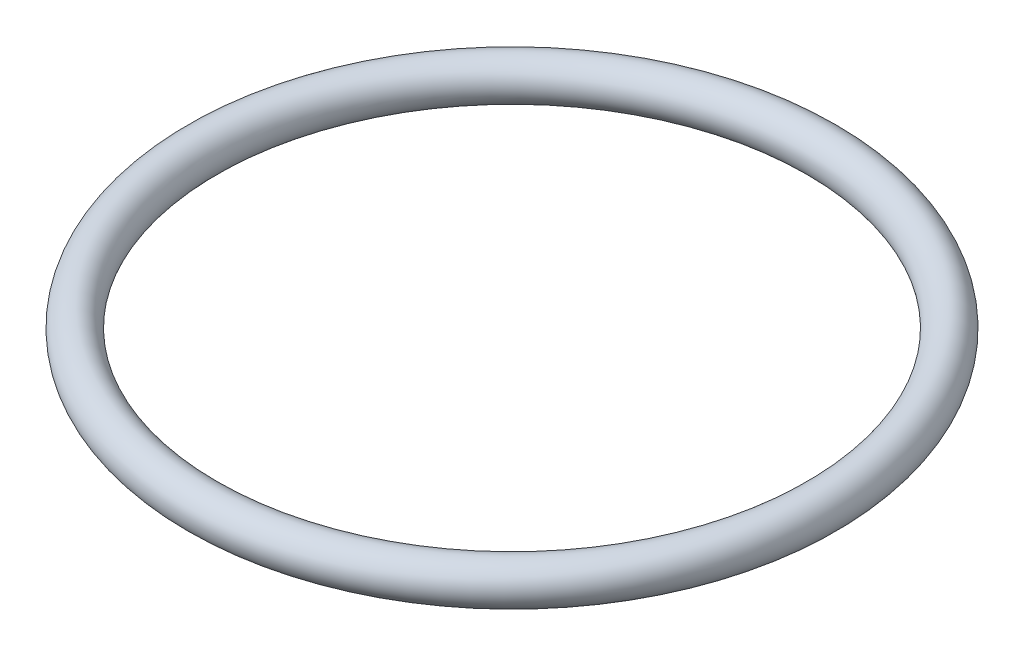
SolidWorks part; units mm, degrees
material "1060 Alloy"
ref_plane "Front Plane" through (0, 0, 0) normal (0, 0, 1) x (1, 0, 0)
ref_plane "Top Plane" through (0, 0, 0) normal (0, 1, 0) x (1, 0, 0)
ref_plane "Right Plane" through (0, 0, 0) normal (1, 0, 0) x (0, 0, -1)
sketch "Sketch1" plane through (0, 0, 0) normal (0, 0, 1) x (1, 0, 0)
  line L0 (55, 0) -> (-55, 0) construction
  circle A0 centre (190, 0) radius 12.5
  dimension "D2" = 25
  dimension "D1" = 190
ref_axis "Axis1" through (0, 16.5, 0) along (0, -1, 0)
revolve "Revolve1" add sketch "Sketch1" angle 360 mid plane about axis through (0, 16.5, 0) along (0, -1, 0)
shell "Shell2" thickness 3
